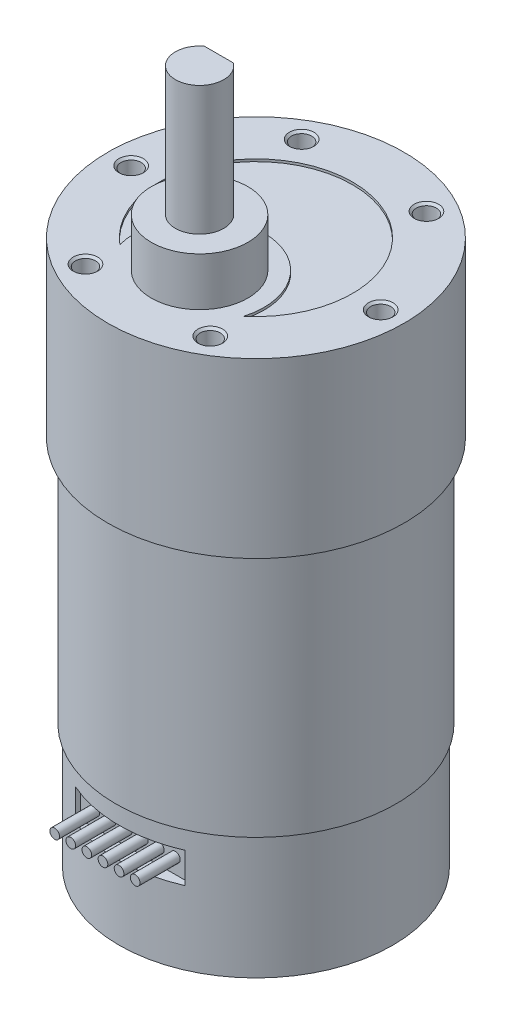
SolidWorks part; units mm, degrees
ref_plane "前视基准面" through (0, 0, 0) normal (0, 0, 1) x (1, 0, 0)
ref_plane "上视基准面" through (0, 0, 0) normal (0, 1, 0) x (1, 0, 0)
ref_plane "右视基准面" through (0, 0, 0) normal (1, 0, 0) x (0, 0, -1)
sketch "草图1" plane through (0, 0, 0) normal (0, 1, 0) x (1, 0, 0)
  circle A0 centre (0, 0) radius 18.4
  dimension "D1" = 36.8
extrude "凸台-拉伸1" add sketch "草图1" against normal blind 21.5
sketch "草图2" plane through (0, 0, 0) normal (0, 1, 0) x (1, 0, 0)
  circle A0 centre (0, -7) radius 6
  dimension "D1" = 12
  dimension "D2" = 7
extrude "凸台-拉伸2" add sketch "草图2" along normal blind 6
sketch "草图3" plane through (0, 6, 0) normal (0, 1, 0) x (1, 0, 0)
  circle A0 centre (0, -7) radius 3
  dimension "D1" = 6
extrude "凸台-拉伸3" add sketch "草图3" along normal blind 16
sketch "草图4" plane through (0, 22, 0) normal (0, 1, 0) x (1, 0, 0)
  line L0 (0, -10) -> (0, -4) construction
  line L1 (-2.5, -3.6) -> (2.5, -3.6)
  line L2 (-2.5, -3.6) -> (-2.5, -4.6)
  line L3 (-2.5, -4.6) -> (2.5, -4.6)
  line L4 (2.5, -3.6) -> (2.5, -4.6)
  circle A0 centre (0, -7) radius 3 construction
  circle A1 centre (0, -7) radius 3 construction
  point P11 (0, -4.6)
  dimension "D1" = 5.4
  dimension "D2" = 1
  dimension "D3" = 5
extrude "切除-拉伸1" cut sketch "草图4" against normal blind 11.85
sketch "草图5" plane through (0, -21.5, 0) normal (0, -1, 0) x (1, 0, 0)
  circle A0 centre (0, 0) radius 17.4
  dimension "D1" = 34.8
extrude "凸台-拉伸4" add sketch "草图5" along normal blind 30.7
sketch "草图6" plane through (0, -52.2, 0) normal (0, -1, 0) x (1, 0, 0)
  circle A0 centre (0, 0) radius 17
  dimension "D1" = 34
extrude "凸台-拉伸5" add sketch "草图6" along normal blind 15.4
sketch "草图7" plane through (0, 0, 0) normal (0, 0, 1) x (1, 0, 0)
  line L0 (-17, -52.2) -> (17, -52.2) construction
  line L1 (6.8, -58.5) -> (-6.8, -58.5)
  line L2 (6.8, -58.5) -> (6.8, -54.7)
  line L3 (6.8, -54.7) -> (-6.8, -54.7)
  line L4 (-6.8, -58.5) -> (-6.8, -54.7)
  line L5 (6.8, -58.5) -> (-6.8, -54.7) construction
  line L6 (6.8, -54.7) -> (-6.8, -58.5) construction
  point P0 (0, -56.6)
  dimension "D1" = 13.6
  dimension "D2" = 3.8
  dimension "D3" = 2.5
extrude "切除-拉伸2" cut sketch "草图7" along normal through all from offset 15
sketch "草图8" plane through (0, 0, 15) normal (0, 0, 1) x (1, 0, 0)
  line L0 (6.8, -56.6) -> (-6.8, -56.6) construction
  line L1 (6.8, -58.5) -> (6.8, -54.7) construction
  line L2 (-6.8, -54.7) -> (-6.8, -58.5) construction
  line L3 (0, -56.6) -> (0, -54.7) construction
  line L4 (6.8, -54.7) -> (-6.8, -54.7) construction
  circle A0 centre (-5, -56.6) radius 0.6
  circle A1 centre (-3, -56.6) radius 0.6
  circle A2 centre (-1, -56.6) radius 0.6
  circle A3 centre (1, -56.6) radius 0.6
  circle A4 centre (3, -56.6) radius 0.6
  circle A5 centre (5, -56.6) radius 0.6
  dimension "D2" = 1.2
  dimension "D1" = 2
  dimension "D3" = 2
  dimension "D4" = 2
extrude "凸台-拉伸6" add sketch "草图8" along normal blind 5
hole_wizard "M3 螺纹孔1" positions "草图9" profile "草图11" tap size "M3" standard "GB"
sketch "草图9" plane through (0, 0, 0) normal (0, 1, 0) x (1, 0, 0)
  line L1 (0, 0) -> (0, 8.1103) construction
  circle A0 centre (0, 0) radius 15.5 construction
  point P0 (-7.75, 13.4234)
  point P2 (15.5, 0)
  point P4 (7.75, -13.4234)
  point P6 (-7.75, -13.4234)
  point P8 (-15.5, 0)
  point P10 (7.75, 13.4234)
  dimension "D1" = 15.5
  dimension "D2" = 31
  dimension "D3" = 15.5
sketch "草图11" plane through (-7.75, 0, -13.4234) normal (1, 0, 0) x (0, 0, 1)
  line L0 (0, 0) -> (0, 9.2511)
  line L1 (0, 9.2511) -> (1.25, 8.5)
  line L2 (1.25, 8.5) -> (1.25, 0.275)
  line L3 (1.25, 0.275) -> (1.525, 0)
  line L5 (1.525, 0) -> (0, 0)
  line L6 (-1.25, 0.275) -> (-1.525, 0) construction
  line L10 (0, 9.2511) -> (-1.25, 8.5) construction
  line L11 (0, -6.35) -> (0, 107.95) construction
  dimension "螺纹孔钻头直径" = 2.5
  dimension "螺纹孔钻头深度" = 8.5
  dimension "近端锥形沉头孔直径" = 3.05
  dimension "近端锥形沉头孔角度" = 90
  dimension "导头角度" = 118
cosmetic thread "孔螺蚊线1" parameters "D1"=6, "D2"=3
cosmetic thread "孔螺蚊线2" parameters "D1"=6, "D2"=3
cosmetic thread "孔螺蚊线3" parameters "D1"=6, "D2"=3
cosmetic thread "孔螺蚊线4" parameters "D1"=6, "D2"=3
cosmetic thread "孔螺蚊线5" parameters "D1"=6, "D2"=3
cosmetic thread "孔螺蚊线6" parameters "D1"=6, "D2"=3
sketch "草图12" plane through (0, 0, 0) normal (0, 1, 0) x (1, 0, 0)
  arc A0 (7.6875, -9.2143) -> (-7.6875, -9.2143) centre (0, 0) ccw
  arc A1 (7.6875, -9.2143) -> (-7.6875, -9.2143) centre (0, -7) ccw
  dimension "D1" = 8
  dimension "D2" = 12
extrude "切除-拉伸3" cut sketch "草图12" against normal blind 0.3
